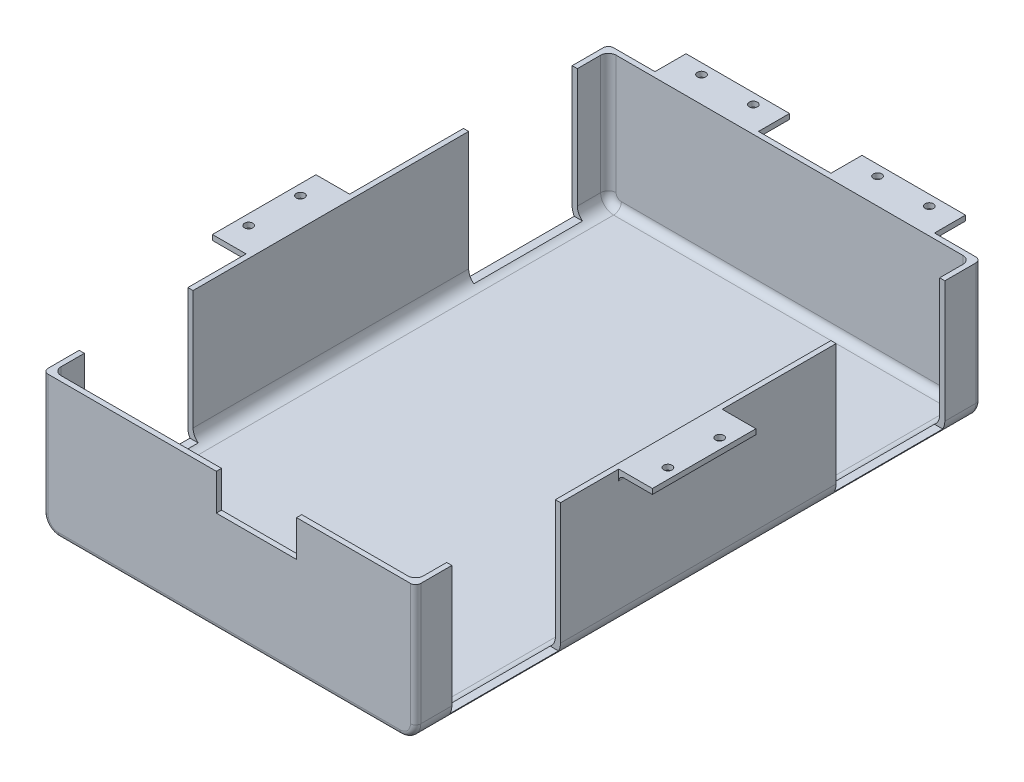
SolidWorks part; units mm, degrees
ref_plane "前视基准面" through (0, 0, 0) normal (0, 0, 1) x (1, 0, 0)
ref_plane "上视基准面" through (0, 0, 0) normal (0, 1, 0) x (1, 0, 0)
ref_plane "右视基准面" through (0, 0, 0) normal (1, 0, 0) x (0, 0, -1)
sketch "草图1" plane through (0, 0, 0) normal (0, 0, 1) x (1, 0, 0)
  line L0 (-68, 0) -> (68, 0) construction
  line L1 (-2, 0) -> (-2, 31.3072) construction
  line L2 (-68, 0) -> (64, 0)
  line L4 (-67, 2) -> (63, 2)
  line L7 (68, 7) -> (68, 53)
  line L8 (68, 53) -> (70, 53)
  line L9 (70, 6) -> (70, 53)
  line L10 (-72, 53) -> (-74, 53)
  line L11 (-74, 6) -> (-74, 53)
  line L13 (-72, 7) -> (-72, 53)
  arc A0 (68, 7) -> (63, 2) centre (63, 7) cw
  arc A1 (70, 6) -> (64, 0) centre (64, 6) cw
  arc A2 (-72, 7) -> (-67, 2) centre (-67, 7) ccw
  arc A3 (-74, 6) -> (-68, 0) centre (-68, 6) ccw
  point P4 (0, 0)
  point P19 (68, 2)
  point P25 (-72, 2)
  dimension "D3" = 5
  dimension "D5" = 6
  dimension "D6" = 5
  dimension "D7" = 6
  dimension "D1" = 2
  dimension "D2" = 140
  dimension "D4" = 2
  dimension "D8" = 47
  dimension "D9" = 2
extrude "凸台-拉伸1" add sketch "草图1" along normal blind 214.5
sketch "草图2" plane through (0, 0, 214.5) normal (0, 0, 1) x (1, 0, 0)
  line L0 (-68, 0) -> (64, 0) construction
  line L1 (-68, 0) -> (64, 0)
  line L2 (-74, 6) -> (-74, 53)
  line L3 (-74, 53) -> (70, 53)
  line L4 (70, 6) -> (70, 53)
  arc A0 (-68, 0) -> (-74, 6) centre (-68, 6) cw
  arc A1 (64, 0) -> (70, 6) centre (64, 6) ccw
  point P9 (-74, 0)
  dimension "D2" = 6
  dimension "D3" = 6
  dimension "D1" = 144
extrude "凸台-拉伸2" add sketch "草图2" along normal blind 2
sketch "草图3" plane through (0, 0, 0) normal (0, 0, -1) x (-1, 0, 0)
  line L0 (68, 0) -> (-64, 0) construction
  line L1 (-64, 0) -> (68, 0)
  line L2 (-70, 6) -> (-70, 53)
  line L3 (-70, 53) -> (74, 53)
  line L4 (74, 6) -> (74, 53)
  line L5 (74, 53) -> (74, 6) construction
  arc A0 (-64, 0) -> (-70, 6) centre (-64, 6) cw
  arc A1 (68, 0) -> (74, 6) centre (68, 6) ccw
  point P10 (-70, 0)
  dimension "D2" = 6
  dimension "D3" = 6
  dimension "D1" = 144
  dimension "D4" = 53
extrude "凸台-拉伸3" add sketch "草图3" along normal blind 2
fillet "圆角2" radius 3 5 edges at (-72, 30, 214.5) (-70.5355, 3.4645, 214.5) (-2, 2, 214.5) (66.5355, 3.4645, 214.5) (68, 30, 214.5)
fillet "圆角3" radius 3 5 edges at (68, 30, 0) (66.5355, 3.4645, 0) (-2, 2, 0) (-70.5355, 3.4645, 0) (-72, 30, 0)
sketch "草图6" plane through (0, 53, 0) normal (0, 1, 0) x (1, 0, 0)
  line L0 (-2, 88.3738) -> (-2, -84.3738) construction
  line L2 (-74, 2) -> (70, 2) construction
  line L3 (-56, 2) -> (-16, 2)
  line L4 (-56, 2) -> (-56, 14)
  line L5 (-56, 14) -> (-16, 14)
  line L6 (-16, 2) -> (-16, 14)
  line L7 (-56, 10) -> (-16, 10) construction
  line L11 (-74, -216.5) -> (-74, 2) construction
  line L12 (-74, -98) -> (-87, -98)
  line L13 (-74, -98) -> (-74, -138)
  line L14 (-74, -138) -> (-87, -138)
  line L15 (-87, -98) -> (-87, -138)
  line L16 (-83, -98) -> (-83, -138) construction
  line L21 (70, -138) -> (83, -138)
  line L22 (83, -98) -> (83, -138)
  line L23 (70, -98) -> (83, -98)
  line L24 (70, -98) -> (70, -138)
  line L25 (52, 14) -> (12, 14)
  line L26 (12, 2) -> (12, 14)
  line L27 (52, 2) -> (12, 2)
  line L28 (52, 2) -> (52, 14)
  circle A8 centre (-83, -108) radius 1.6
  circle A9 centre (-83, -128) radius 1.6
  circle A10 centre (79, -128) radius 1.6
  circle A11 centre (79, -108) radius 1.6
  circle A12 centre (-46, 10) radius 1.6
  circle A13 centre (-26, 10) radius 1.6
  circle A14 centre (42, 10) radius 1.6
  circle A15 centre (22, 10) radius 1.6
  point P3 (-2, 2)
  dimension "D2" = 4
  dimension "D3" = 3.2
  dimension "D10" = 3.2
  dimension "D11" = 3.2
  dimension "D5" = 3.2
  dimension "D1" = 12
  dimension "D4" = 40
  dimension "D6" = 10
  dimension "D7" = 14
  dimension "D8" = 13
  dimension "D9" = 40
  dimension "D12" = 10
  dimension "D13" = 10
  dimension "D14" = 100
  dimension "D15" = 10
  dimension "D16" = 4
extrude "凸台-拉伸4" add sketch "草图6" against normal blind 2
sketch "草图8" plane through (0, 0, 216.5) normal (0, 0, 1) x (1, 0, 0)
  line L0 (-2, 53) -> (-2, 0) construction
  line L1 (70, 53) -> (-74, 53) construction
  line L3 (-7, 53) -> (24, 53)
  line L4 (-7, 53) -> (-7, 39)
  line L5 (-7, 39) -> (24, 39)
  line L6 (24, 53) -> (24, 39)
  dimension "D1" = 31
  dimension "D2" = 5
  dimension "D3" = 14
extrude "切除-拉伸2" cut sketch "草图8" against normal blind 10
fillet "圆角4" radius 2 4 edges at (70, 51, 118) (32, 51, -2) (-36, 51, -2) (-74, 51, 118)
fillet "圆角5" radius 2 10 edges at (-74, 29.5, -2) (-72.2426, 1.7574, -2) (-2, 0, -2) (68.2426, 1.7574, -2) (70, 29.5, 216.5) (68.2426, 1.7574, 216.5) (-2, 0, 216.5) (-72.2426, 1.7574, 216.5) (70, 29.5, -2) (-74, 29.5, 216.5)
sketch "草图9" plane through (70, 0, 0) normal (1, 0, 0) x (0, 0, -1)
  line L0 (-214.5, 53) -> (-202.5, 53) construction
  line L1 (-214.5, 53) -> (-138, 53) construction
  line L3 (-202.5, 53) -> (-160.5, 53)
  line L4 (-202.5, 53) -> (-202.5, 3)
  line L5 (-202.5, 3) -> (-160.5, 3)
  line L6 (-160.5, 53) -> (-160.5, 3)
  dimension "D1" = 12
  dimension "D2" = 42
  dimension "D3" = 50
extrude "切除-拉伸3" cut sketch "草图9" against normal through all
sketch "草图10" plane through (70, 0, 0) normal (1, 0, 0) x (0, 0, -1)
  line L0 (0, 53) -> (-12, 53) construction
  line L1 (-98, 53) -> (0, 53) construction
  line L3 (-12, 53) -> (-54, 53)
  line L4 (-12, 53) -> (-12, 3)
  line L5 (-12, 3) -> (-54, 3)
  line L6 (-54, 53) -> (-54, 3)
  dimension "D1" = 12
  dimension "D2" = 42
  dimension "D3" = 50
extrude "切除-拉伸4" cut sketch "草图10" against normal through all
